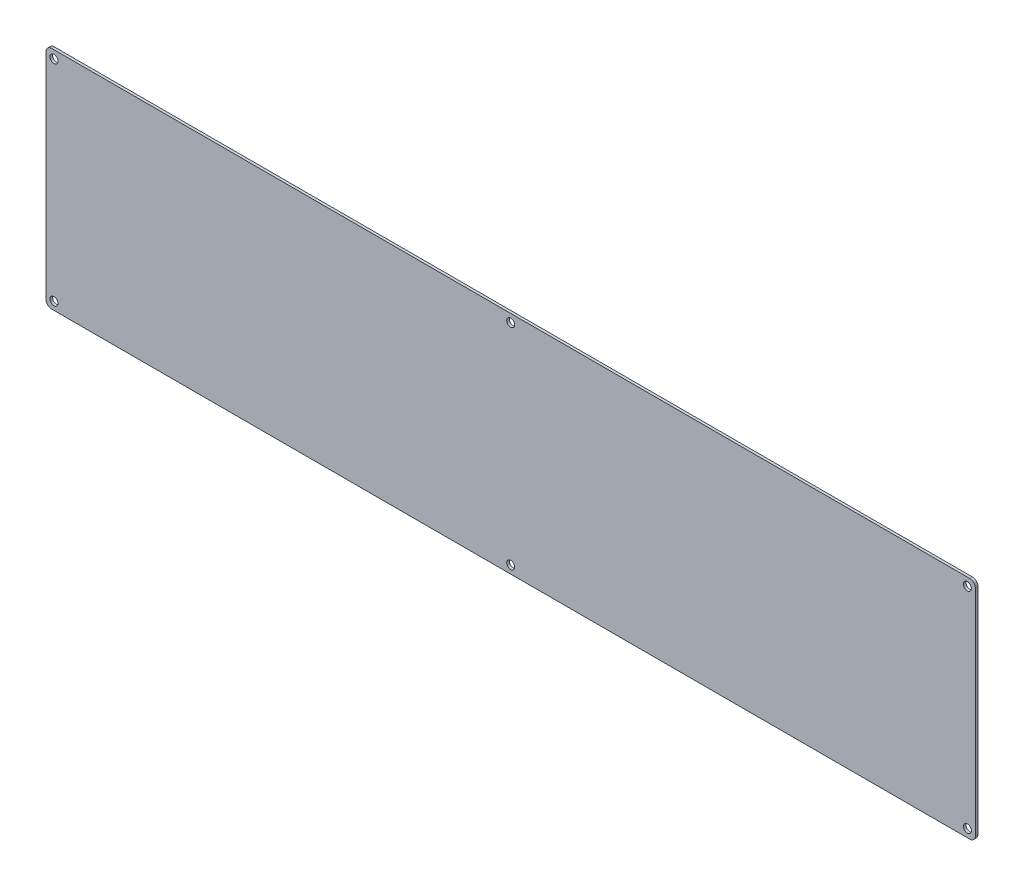
SolidWorks part; units mm, degrees
ref_plane "正面" through (0, 0, 0) normal (0, 0, 1) x (1, 0, 0)
ref_plane "平面" through (0, 0, 0) normal (0, 1, 0) x (1, 0, 0)
ref_plane "右側面" through (0, 0, 0) normal (1, 0, 0) x (0, 0, -1)
sketch "ｽｹｯﾁ1" plane through (0, 0, 0) normal (0, 0, 1) x (1, 0, 0)
  line L1 (5, 0) -> (810, 0)
  line L2 (0, 5) -> (0, 193)
  line L3 (5, 198) -> (810, 198)
  line L4 (815, 5) -> (815, 193)
  arc A0 (0, 193) -> (5, 198) centre (5, 193) cw
  arc A1 (810, 198) -> (815, 193) centre (810, 193) cw
  arc A2 (810, 0) -> (815, 5) centre (810, 5) ccw
  arc A3 (5, 0) -> (0, 5) centre (5, 5) cw
  point P13 (0, 0)
  dimension "D1" = 5
extrude "ﾎﾞｽ - 押し出し1" add sketch "ｽｹｯﾁ1" along normal blind 2.3
sketch "ｽｹｯﾁ2" plane through (0, 0, 0) normal (0, 0, 1) x (1, 0, 0)
  circle A0 centre (7, 7) radius 3.5
  circle A1 centre (7, 191) radius 3.5
  circle A2 centre (407.5, 7) radius 3.5
  circle A3 centre (407.5, 191) radius 3.5
  circle A4 centre (808, 7) radius 3.5
  circle A5 centre (808, 191) radius 3.5
extrude "ｶｯﾄ - 押し出し1" cut sketch "ｽｹｯﾁ2" against normal through all and the other way through all
